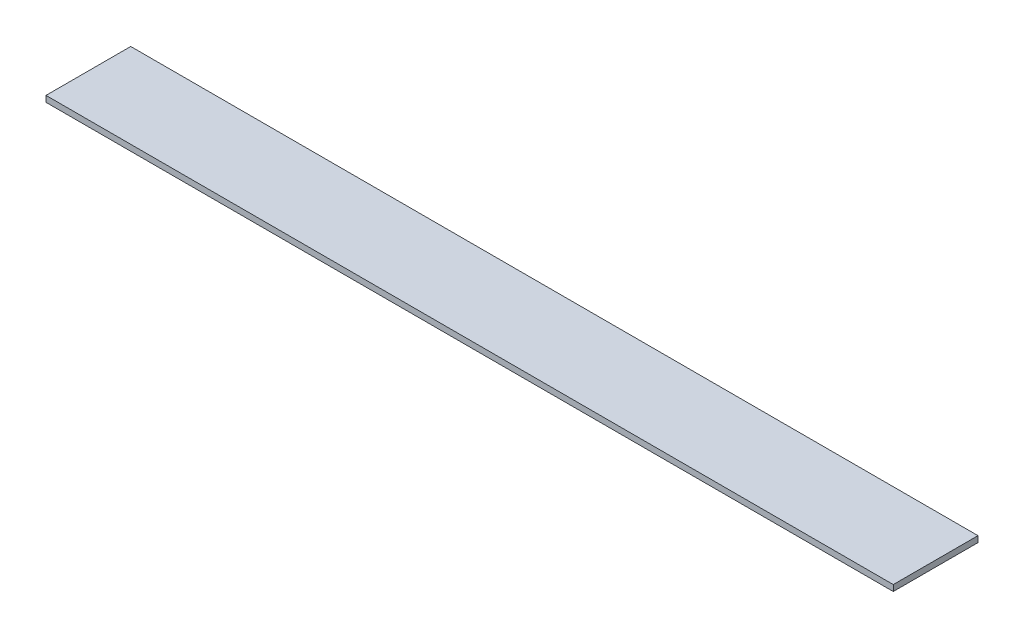
SolidWorks part; units mm, degrees
ref_plane "Front Plane" through (0, 0, 0) normal (0, 0, 1) x (1, 0, 0)
ref_plane "Top Plane" through (0, 0, 0) normal (0, 1, 0) x (1, 0, 0)
ref_plane "Right Plane" through (0, 0, 0) normal (1, 0, 0) x (0, 0, -1)
sketch "Sketch1" plane through (0, 0, 0) normal (1, 0, 0) x (0, 0, -1)
  line L1 (0, 0) -> (140, 0)
  line L2 (0, 0) -> (0, -10)
  line L3 (0, -10) -> (140, -10)
  line L4 (140, 0) -> (140, -10)
  dimension "D1" = 140
  dimension "D2" = 10
extrude "Boss-Extrude1" add sketch "Sketch1" along normal blind 1400 contours L1 L4 L3 L2
